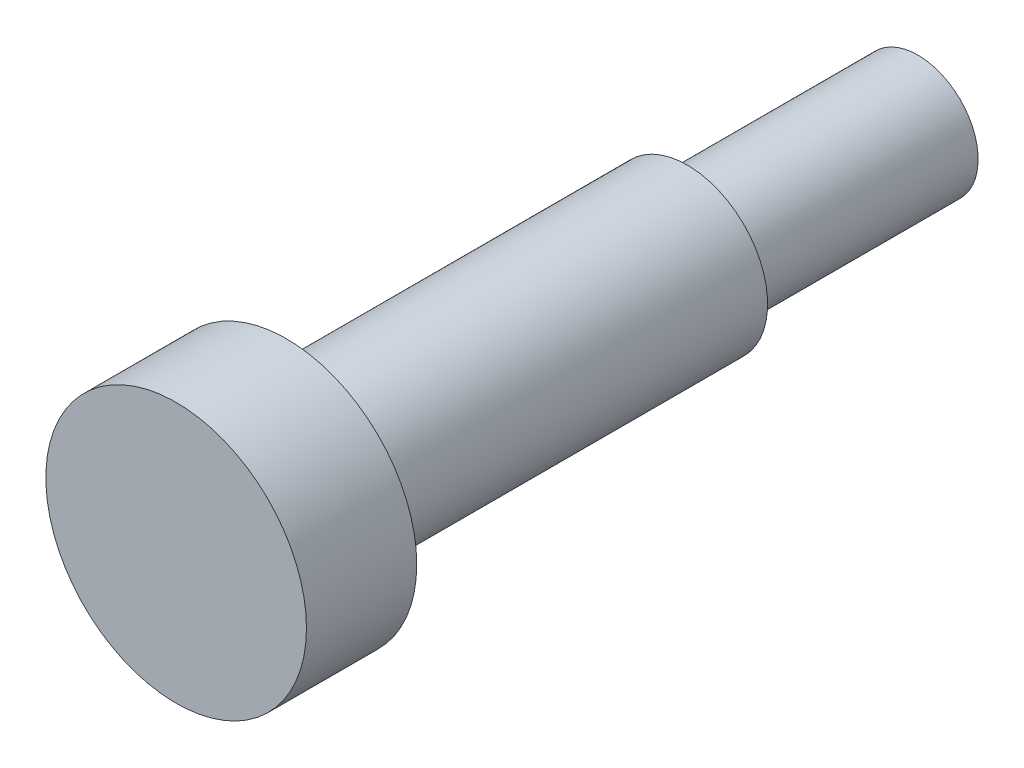
SolidWorks part; units mm, degrees
ref_plane "前视基准面" through (0, 0, 0) normal (0, 0, 1) x (1, 0, 0)
ref_plane "上视基准面" through (0, 0, 0) normal (0, 1, 0) x (1, 0, 0)
ref_plane "右视基准面" through (0, 0, 0) normal (1, 0, 0) x (0, 0, -1)
other "Configuration Table"
sketch "草图1" plane through (0, 0, 0) normal (0, 0, 1) x (1, 0, 0)
  circle A0 centre (0, 0) radius 6.5
  dimension "D1" = 13
extrude "凸台-拉伸1" add sketch "草图1" against normal blind 5.5
sketch "草图2" plane through (0, 0, -5.5) normal (0, 0, -1) x (-1, 0, 0)
  circle A0 centre (0, 0) radius 4
  dimension "D1" = 8
extrude "凸台-拉伸2" add sketch "草图2" along normal blind 20
sketch "草图3" plane through (0, 0, -25.5) normal (0, 0, -1) x (-1, 0, 0)
  circle A0 centre (0, 0) radius 3
  dimension "D1" = 6
extrude "凸台-拉伸3" add sketch "草图3" along normal blind 11.5
cosmetic thread "装饰螺纹线1" parameters "D2"=5
